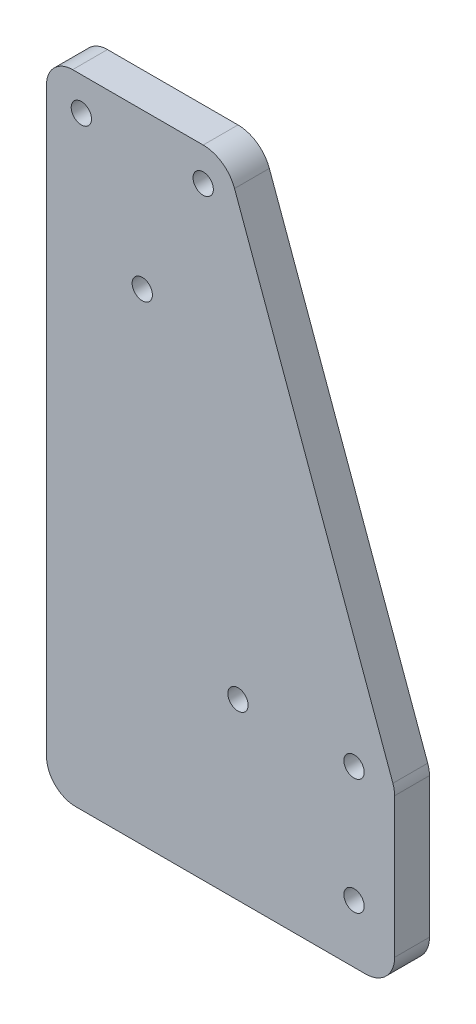
SolidWorks part; units mm, degrees
ref_plane "Plano frontal" through (0, 0, 0) normal (0, 0, 1) x (1, 0, 0)
ref_plane "Plano superior" through (0, 0, 0) normal (0, 1, 0) x (1, 0, 0)
ref_plane "Plano direito" through (0, 0, 0) normal (1, 0, 0) x (0, 0, -1)
sketch "Esboço1" plane through (0, 0, 0) normal (0, 0, 1) x (1, 0, 0)
  line L5 (-30, -55) -> (30, -55)
  line L6 (-30, -55) -> (-30, 55)
  line L7 (-30, 55) -> (30, 55)
  line L8 (30, -55) -> (30, 55)
  line L9 (-30, -55) -> (30, 55) construction
  line L10 (-30, 55) -> (30, -55) construction
  line L14 (23, 5) -> (23, -25) construction
  circle A0 centre (23, -45) radius 1.75
  circle A1 centre (23, -25) radius 1.75
  circle A2 centre (3, -25) radius 1.75
  point P0 (0, 0)
  dimension "D4" = 3.5
  dimension "D7" = 20
  dimension "D1" = 110
  dimension "D2" = 60
  dimension "D3" = 7
  dimension "D5" = 20
  dimension "D6" = 10
extrude "Ressalto-extrusão1" add sketch "Esboço1" along normal blind 6
sketch "Esboço2" plane through (0, 0, 6) normal (0, 0, 1) x (1, 0, 0)
  line L1 (30, 55) -> (-30, 55) construction
  line L3 (-30, 49) -> (30, 49) construction
  line L4 (-30, 55) -> (-30, -55) construction
  line L5 (30, -55) -> (30, 55) construction
  line L7 (-30, 55) -> (-30, -55) construction
  circle A0 centre (-24, 49) radius 1.75
  circle A1 centre (-3, 49) radius 1.75
  circle A2 centre (-13.5, 28) radius 1.75
  dimension "D2" = 21
  dimension "D3" = 3.5
  dimension "D4" = 10.5
  dimension "D1" = 6
  dimension "D5" = 6
  dimension "D6" = 21
extrude "Corte-extrusão1" cut sketch "Esboço2" against normal through all
sketch "Esboço3" plane through (0, 0, 6) normal (0, 0, 1) x (1, 0, 0)
  line L0 (-13.5, 28) -> (-13.5, 49) construction
  line L1 (-3, 49) -> (-24, 49) construction
  circle A0 centre (-13.5, 38.5) radius 4.25
  point P13 (-13.5, 49)
  dimension "D1" = 8.5
  dimension "D2" = 10.5
extrude "Corte-extrusão2" [suppressed] cut sketch "Esboço3" against normal through all contours A0
sketch "Esboço4" plane through (0, 0, 0) normal (0, 0, -1) x (-1, 0, 0)
  line L0 (3, 54.75) -> (25.5, 54.75)
  line L1 (-21.25, -25) -> (-30, -25) construction
  line L2 (-30, -55) -> (-30, 55) construction
  line L3 (-30, -25) -> (-2.4044, 50.9633)
  line L4 (30, -55) -> (-30, -55) construction
  line L5 (0, -55) -> (0, 0) construction
  line L6 (30, 18.5479) -> (30, 50.25)
  line L7 (-30, -25) -> (-45.5701, -25)
  line L8 (-45.5701, -25) -> (-45.5701, 63.6587)
  line L9 (-45.5701, 63.6587) -> (51.2135, 63.6587)
  line L10 (51.2135, 63.6587) -> (51.2135, 18.5479)
  line L11 (51.2135, 18.5479) -> (30, 18.5479)
  line L12 (30, 55) -> (30, -55) construction
  line L13 (-2.4044, 50.9633) -> (30, 50.25) construction
  arc A0 (3, 54.75) -> (-2.4044, 50.9633) centre (3, 49) ccw
  circle A1 centre (3, 49) radius 1.75 construction
  arc A2 (30, 50.25) -> (25.5, 54.75) centre (25.5, 50.25) ccw
  circle A3 centre (-23, -25) radius 1.75 construction
  dimension "D1" = 4
  dimension "D2" = 30
  dimension "D3" = 4.5
extrude "Corte-extrusão3" cut sketch "Esboço4" against normal through all
fillet "Filete1" radius 5 3 edges at (30, -25, 3) (30, -55, 3) (-30, -55, 3)
